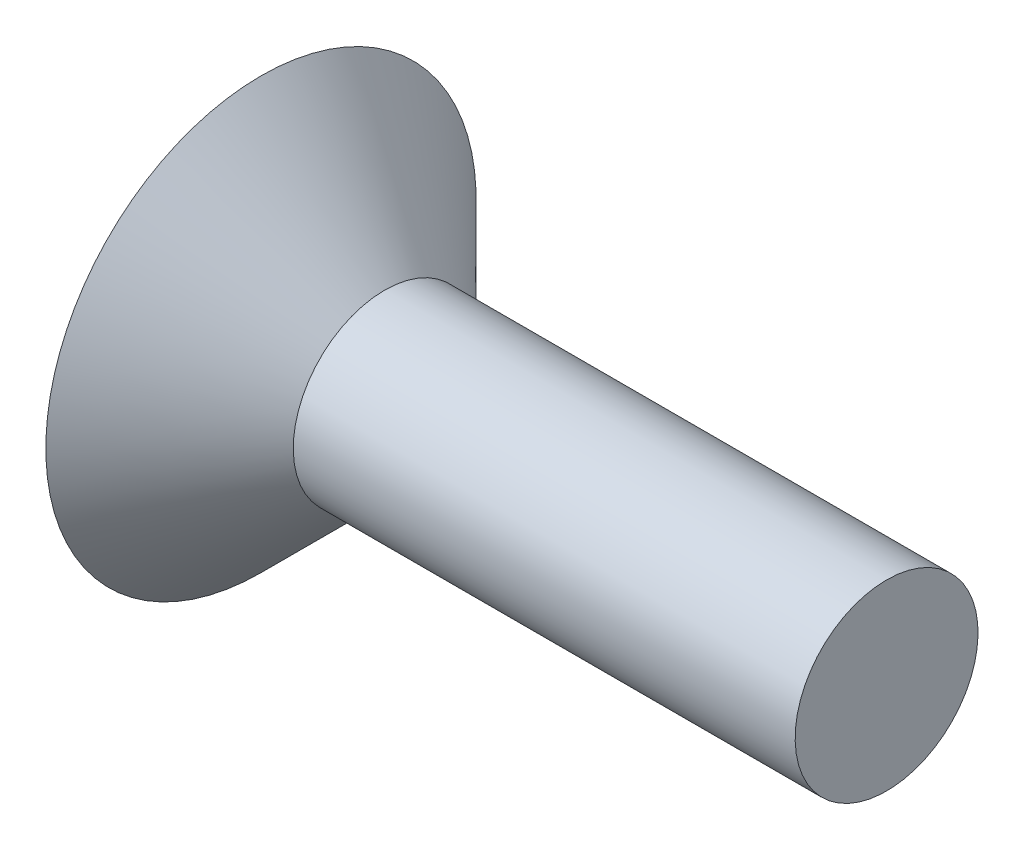
SolidWorks part; units mm, degrees
ref_plane "Ön Düzlem" through (0, 0, 0) normal (0, 0, 1) x (1, 0, 0)
ref_plane "Üst Düzlem" through (0, 0, 0) normal (0, 1, 0) x (1, 0, 0)
ref_plane "Sağ Düzlem" through (0, 0, 0) normal (1, 0, 0) x (0, 0, -1)
sketch "Çizim1" plane through (0, 0, 0) normal (0, 0, 1) x (1, 0, 0)
  line L0 (0, 0) -> (0, 4)
  line L1 (0, 4) -> (2.3, 1.7)
  line L2 (2.3, 1.7) -> (11.6308, 1.7)
  line L3 (11.6308, 1.7) -> (11.6308, 0)
  line L4 (11.6308, 0) -> (0, 0)
  dimension "D1" = 4
  dimension "D2" = 45
  dimension "D4" = 2.3
revolve "Döndür1" add sketch "Çizim1" angle 360 about L4
sketch "Çizim2" plane through (0, 0, 0) normal (-1, 0, 0) x (0, 0, 1)
  line L1 (1.1547, -2) -> (2.3094, 0)
  line L2 (2.3094, 0) -> (1.1547, 2)
  line L3 (1.1547, 2) -> (-1.1547, 2)
  line L4 (-1.1547, 2) -> (-2.3094, 0)
  line L5 (-2.3094, 0) -> (-1.1547, -2)
  line L6 (-1.1547, -2) -> (1.1547, -2)
  circle A0 centre (0, 0) radius 2 construction
  dimension "D1" = 4
extrude "Kes-Ekstrüzyon1" cut sketch "Çizim2" against normal blind 1.5
